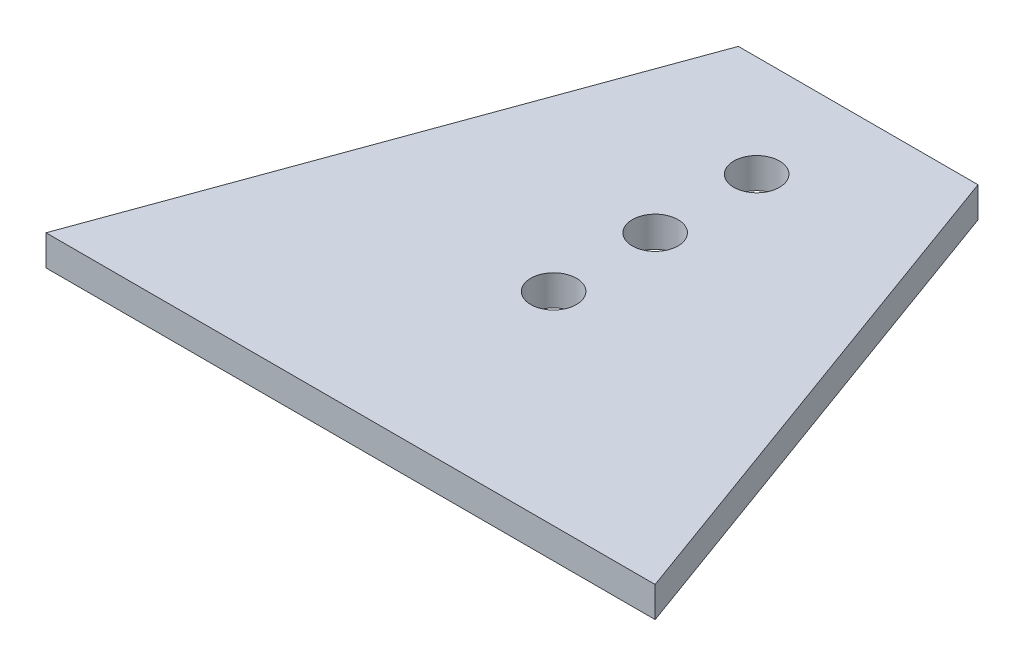
SolidWorks part; units mm, degrees
ref_plane "前视基准面" through (0, 0, 0) normal (0, 0, 1) x (1, 0, 0)
ref_plane "上视基准面" through (0, 0, 0) normal (0, 1, 0) x (1, 0, 0)
ref_plane "右视基准面" through (0, 0, 0) normal (1, 0, 0) x (0, 0, -1)
sketch "草图1" plane through (0, 0, 0) normal (0, 1, 0) x (1, 0, 0)
  line L0 (0, 0) -> (60, 0)
  line L1 (60, 0) -> (41.8015, 50)
  line L2 (41.8015, 50) -> (18.1985, 50)
  line L3 (18.1985, 50) -> (0, 0)
  line L4 (30, 50) -> (30, 0.7082) construction
  circle A0 centre (30, 30) radius 2.25
  circle A1 centre (30, 20) radius 2.25
  circle A2 centre (30, 40) radius 2.25
  dimension "D5" = 4.5
  dimension "D8" = 10
  dimension "D1" = 50
  dimension "D2" = 70
  dimension "D3" = 70
  dimension "D4" = 60
  dimension "D6" = 20
  dimension "D7" = 10
extrude "凸台-拉伸1" add sketch "草图1" along normal blind 3
